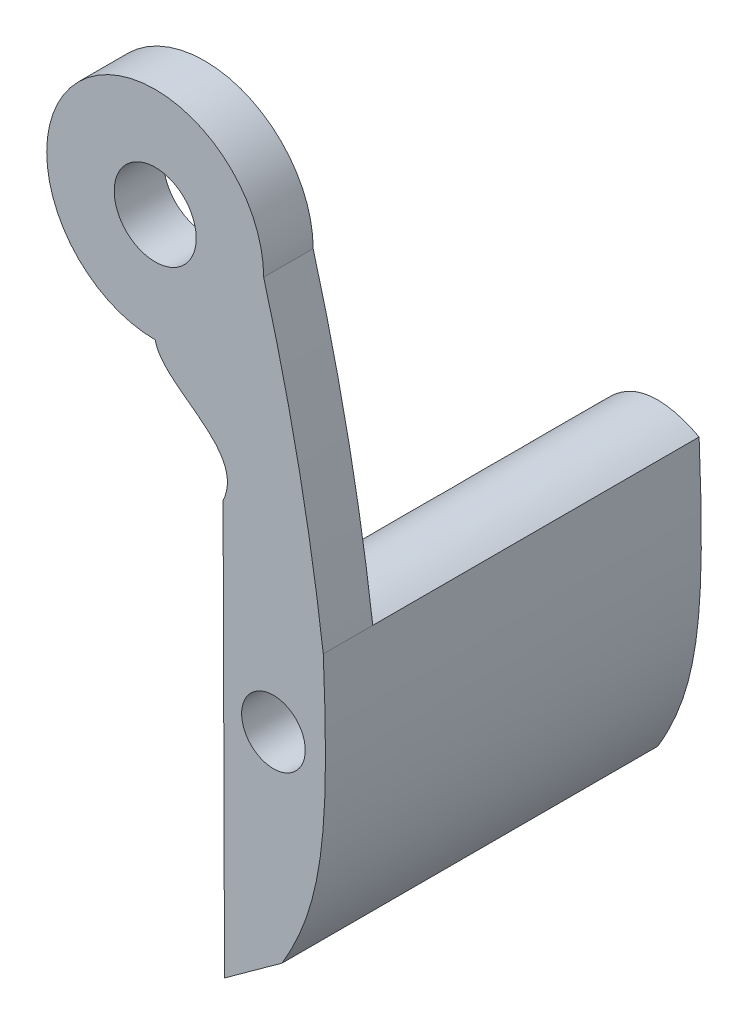
SolidWorks part; units mm, degrees
ref_plane "Front Plane" through (0, 0, 0) normal (0, 0, 1) x (1, 0, 0)
ref_plane "Top Plane" through (0, 0, 0) normal (0, 1, 0) x (1, 0, 0)
ref_plane "Right Plane" through (0, 0, 0) normal (1, 0, 0) x (0, 0, -1)
sketch "Sketch1" plane through (0, 0, 4.9187) normal (0, 0, 1) x (1, 0, 0)
  line L47 (23.6842, -79.8541) -> (27.7517, -76.9116)
  line L48 (23.6087, -58.0448) -> (23.6842, -79.8541)
  line L93 (23.5831, -50.6621) -> (23.6087, -58.0448)
  arc A44 (26.4535, -35.5548) -> (18.783, -43.2252) centre (18.783, -35.5548) ccw
  circle A45 centre (18.783, -35.5548) radius 2.9
  spline S0 degree 2 poles (30.6681, -56.5171) (29.3204, -45.8837) (26.4535, -35.5548) knots 0 0 0 1 1 1
  spline S3 degree 3 poles (27.7517, -76.9116) (30.6656, -71.9964) (31.1322, -67.2565) (30.6681, -56.5171) knots 0.222416 0.222416 0.222416 0.222416 0.766683 0.766683 0.766683 0.766683
  spline S5 degree 3 poles (18.783, -43.2252) (19.3228, -45.8172) (25.2941, -46.9406) (23.5831, -50.6621) knots 0 0 0 0 1 1 1 1
extrude "Boss-Extrude1" add sketch "Sketch1" against normal blind 3.5
sketch "Sketch2" plane through (0, 0, 1.4187) normal (0, 0, -1) x (-1, 0, 0)
  line L4 (-27.7517, -76.9116) -> (-23.6842, -79.8541)
  line L5 (-23.6842, -79.8541) -> (-23.6087, -58.0448)
  parabola Q2 (-23.6087, -58.0448) -> (-30.6681, -56.5171) focus (-27.211, -57.9236) apex (-26.7179, -55.8255)
  spline S2 degree 3 poles (-30.6681, -56.5171) (-31.1322, -67.2565) (-30.6656, -71.9964) (-27.7517, -76.9116) knots 0.222416 0.222416 0.222416 0.222416 0.766683 0.766683 0.766683 0.766683
extrude "Boss-Extrude2" add sketch "Sketch2" along normal blind 23.0769
sketch "Sketch3" plane through (0, 0, 4.9187) normal (0, 0, 1) x (1, 0, 0)
  circle A0 centre (27.1437, -63.0557) radius 2.25
  dimension "D1" = 4.5
extrude "Cut-Extrude1" cut sketch "Sketch3" against normal through all
